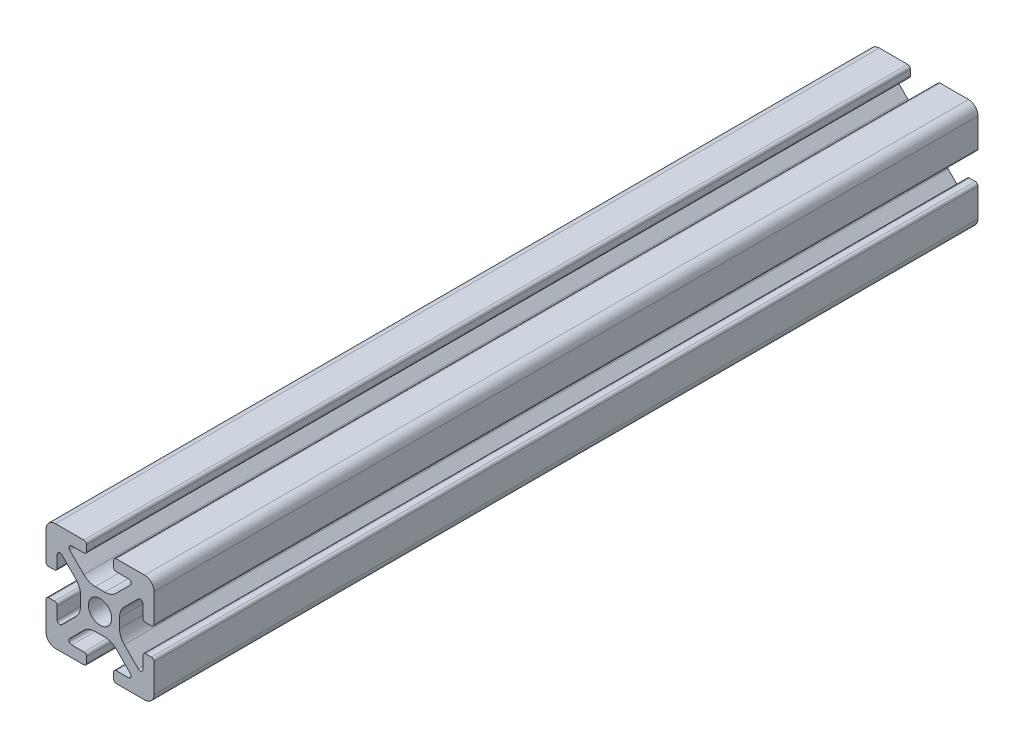
SolidWorks part; units mm, degrees
ref_plane "Front Plane" through (0, 0, 0) normal (0, 0, 1) x (1, 0, 0)
ref_plane "Top Plane" through (0, 0, 0) normal (0, 1, 0) x (1, 0, 0)
ref_plane "Right Plane" through (0, 0, 0) normal (1, 0, 0) x (0, 0, -1)
sketch "Sketch2" plane through (0, 0, 0) normal (0, 0, 1) x (1, 0, 0)
  line L0 (0, 10) -> (0, -10) construction
  line L1 (-10, 0) -> (10, 0) construction
  line L2 (2.5, -10) -> (10, -10)
  line L3 (10, -10) -> (10, -2.5)
  line L4 (2.5, -10) -> (2.5, -7.9246)
  line L5 (2.5, -7.9246) -> (6.4571, -7.9246)
  line L6 (6.4571, -7.9246) -> (2.1325, -3.6)
  line L7 (0, 0) -> (10, -10) construction
  line L8 (10, -2.5) -> (7.9246, -2.5)
  line L9 (7.9246, -2.5) -> (7.9246, -6.4571)
  line L10 (7.9246, -6.4571) -> (3.6, -2.1325)
  line L11 (5.7623, -4.2948) -> (4.2948, -5.7623) construction
  circle A0 centre (0, 0) radius 2.15
  arc A1 (5.25, -7.9246) -> (5.6036, -7.0711) centre (5.25, -7.4246) ccw construction
  point P8 (0, -3.6)
  point P16 (5.0286, -5.0286)
  dimension "Center Hole Diameter" = 4.3
  dimension "D3" = 0.5
  dimension "Rail Height" = 20
  dimension "Rail Width" = 20
  dimension "T-Slot Width" = 5
  dimension "Slot Depth" = 6.4
  dimension "Slot Inner Width" = 11.5
sketch "Sketch3" plane through (0, 0, 0) normal (1, 0, 0) x (0, 0, -1)
  line L0 (-76.2, -10) -> (76.2, -10) construction
  line L1 (-50.8, 0) -> (50.8, 0) construction
  line L2 (0, 10) -> (0, -10) construction
  line L3 (0, 10) -> (0, -10) construction
  point P6 (-50.8, 0)
  point P8 (50.8, 0)
  dimension "Length" = 152.4
  dimension "D1" = 25.4
sketch "Sketch4" plane through (0, 0, 0) normal (0, 0, 1) x (1, 0, 0)
  line L0 (3, -10) -> (8.25, -10)
  line L1 (2.5, -10) -> (10, -10) construction
  line L2 (2.5, -10) -> (2.5, -7.9246) construction
  line L3 (2.5, -7.9246) -> (6.4571, -7.9246) construction
  line L4 (2.5, -8.4246) -> (2.5, -9.5)
  line L5 (3, -7.9246) -> (5.25, -7.9246)
  line L6 (0, -3.6) -> (0.8898, -3.6)
  line L7 (6.4571, -7.9246) -> (2.1325, -3.6) construction
  line L8 (3.0112, -4.4787) -> (5.6036, -7.0711)
  line L9 (10, -10) -> (10, -2.5) construction
  line L10 (7.9246, -6.4571) -> (3.6, -2.1325) construction
  line L11 (7.9246, -2.5) -> (7.9246, -6.4571) construction
  line L12 (7.9246, -5.25) -> (7.9246, -3)
  line L13 (10, -2.5) -> (7.9246, -2.5) construction
  line L14 (8.4246, -2.5) -> (9.5, -2.5)
  line L15 (10, -3) -> (10, -8.25)
  line L16 (7.0711, -5.6036) -> (4.4787, -3.0112)
  line L17 (3.6, 0) -> (3.6, -0.8898)
  line L18 (-10, 0) -> (10, 0) construction
  line L19 (0, -3.6) -> (0, -2.15)
  line L20 (0, 10) -> (0, -10) construction
  line L21 (3.6, 0) -> (2.15, 0)
  arc A0 (2.5, -9.5) -> (3, -10) centre (3, -9.5) ccw
  arc A1 (5.25, -7.9246) -> (5.6036, -7.0711) centre (5.25, -7.4246) ccw construction
  arc A2 (2.5, -8.4246) -> (3, -7.9246) centre (3, -8.4246) cw
  arc A3 (5.25, -7.9246) -> (5.6036, -7.0711) centre (5.25, -7.4246) ccw
  arc A4 (0.8898, -3.6) -> (3.0112, -4.4787) centre (0.8898, -6.6) cw
  arc A5 (8.25, -10) -> (10, -8.25) centre (8.25, -8.25) ccw
  arc A6 (7.0711, -5.6036) -> (7.9246, -5.25) centre (7.4246, -5.25) ccw
  arc A7 (7.9246, -3) -> (8.4246, -2.5) centre (8.4246, -3) cw
  arc A8 (9.5, -2.5) -> (10, -3) centre (9.5, -3) cw
  arc A9 (4.4787, -3.0112) -> (3.6, -0.8898) centre (6.6, -0.8898) cw
  circle A10 centre (0, 0) radius 2.15 construction
  arc A11 (0, -2.15) -> (2.15, 0) centre (0, 0) ccw
  dimension "D1" = 1.75
  dimension "D2" = 3
extrude "Boss-Extrude1" add sketch "Sketch4" along normal mid plane 152.4
mirror "Mirror1" about plane through (0, 0, 0) normal (1, 0, 0) of bodies 134
mirror "Mirror2" about plane through (0, 0, 0) normal (0, 1, 0) of bodies 135
equation "\"D3@Sketch2\"=\"T-Slot Width@Sketch2\"*0.1"
equation "\"D1@Sketch4\"=\"D3@Sketch2\"*3.5"
equation "\"D2@Sketch4\"=\"D3@Sketch2\"*6"
equation "\"D1@Boss-Extrude1\"=\"Length@Sketch3\""
